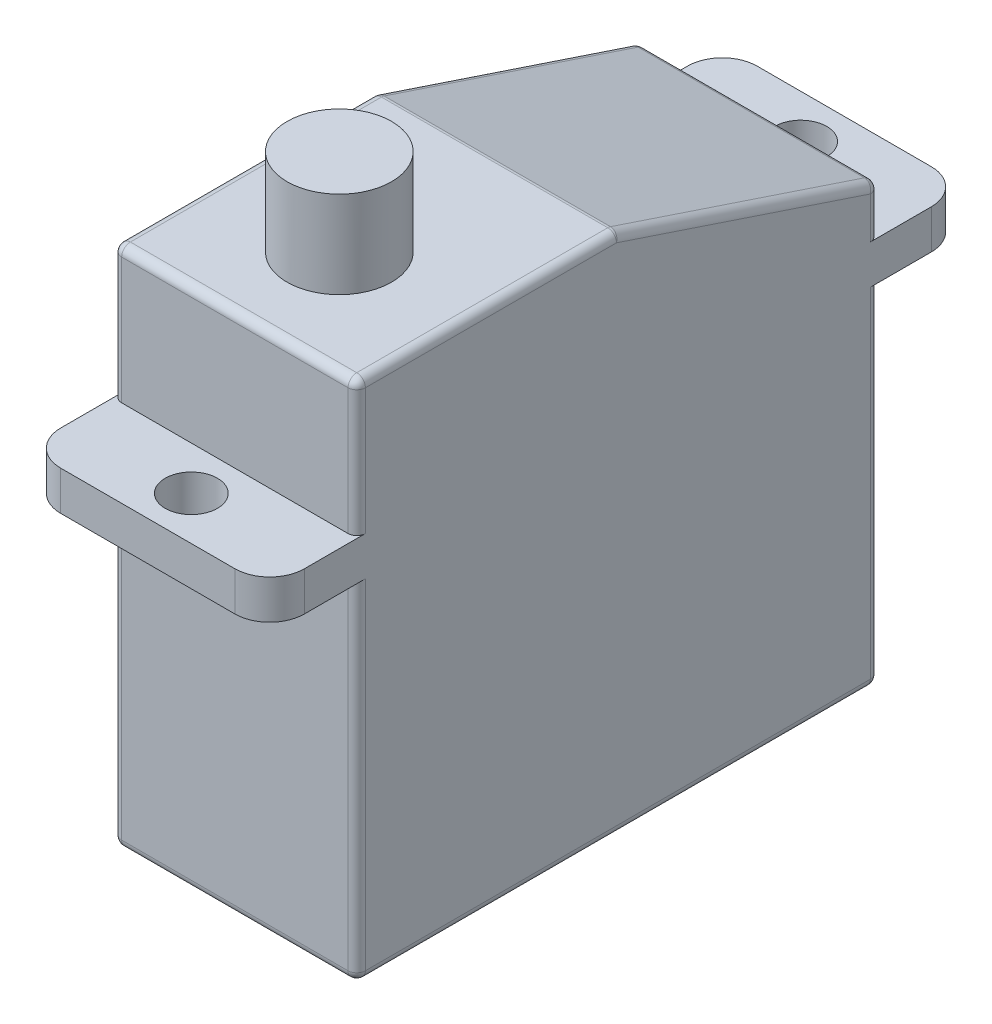
SolidWorks part; units mm, degrees
ref_plane "Front" through (0, 0, 0) normal (0, 0, 1) x (1, 0, 0)
ref_plane "Top" through (0, 0, 0) normal (0, 1, 0) x (1, 0, 0)
ref_plane "Right" through (0, 0, 0) normal (1, 0, 0) x (0, 0, -1)
sketch "Sketch1" plane through (0, 0, 0) normal (0, 1, 0) x (1, 0, 0)
  line L1 (-7, -15) -> (7, -15)
  line L2 (-7, -15) -> (-7, 15)
  line L3 (-7, 15) -> (7, 15)
  line L4 (7, -15) -> (7, 15)
  line L5 (-7, -15) -> (7, 15) construction
  line L6 (-7, 15) -> (7, -15) construction
  point P0 (0, 0)
  dimension "D1" = 14
  dimension "D2" = 30
extrude "Boss-Extrude1" add sketch "Sketch1" along normal blind 30
sketch "Sketch2" plane through (0, 0, 15) normal (0, 0, 1) x (1, 0, 0)
  line L0 (-7, 30) -> (-7, 0) construction
  line L1 (-7, 22.25) -> (7, 22.25)
  line L2 (-7, 22.25) -> (-7, 20)
  line L3 (-7, 20) -> (7, 20)
  line L4 (7, 22.25) -> (7, 20)
  line L5 (7, 30) -> (7, 0) construction
  line L6 (-7, 0) -> (7, 0) construction
  dimension "D1" = 2.25
  dimension "D2" = 20
extrude "Boss-Extrude2" add sketch "Sketch2" along normal blind 5
sketch "Sketch3" plane through (0, 22.25, 0) normal (0, 1, 0) x (1, 0, 0)
  line L0 (0, 0) -> (0, -8.2508) construction
  circle A0 centre (0, -17.5) radius 1.5
  dimension "D2" = 3
  dimension "D1" = 17.5
extrude "Cut-Extrude1" cut sketch "Sketch3" against normal through all
mirror "Mirror1" about plane through (0, 0, 0) normal (0, 0, 1) of "Cut-Extrude1", "Boss-Extrude2"
sketch "Sketch4" plane through (0, 30, 0) normal (0, 1, 0) x (1, 0, 0)
  line L0 (7, -15) -> (7, 15) construction
  line L1 (7, -15) -> (-7, -15) construction
  circle A0 centre (0, -9) radius 3
  dimension "D3" = 6
  dimension "D1" = 7
  dimension "D2" = 6
extrude "Boss-Extrude3" add sketch "Sketch4" along normal blind 5
chamfer "Chamfer1" distance 5 distance2 15 1 edges at (0, 30, -15)
fillet "Fillet1" radius 2 4 edges at (-7, 21.125, 20) (7, 21.125, 20) (-7, 21.125, -20) (7, 21.125, -20)
fillet "Fillet2" radius 0.5 19 edges at (7, 0, 0) (0, 0, -15) (-7, 0, 0) (0, 0, 15) (7, 10, 15) (-7, 10, 15) (-7, 10, -15) (7, 10, -15) (7, 23.625, -15) (-7, 23.625, -15) (-7, 27.5, -7.5) (0, 25, -15) (7, 27.5, -7.5) (0, 30, 0) (7, 30, 7.5) (-7, 30, 7.5) (0, 30, 15) (-7, 26.125, 15) (7, 26.125, 15)
